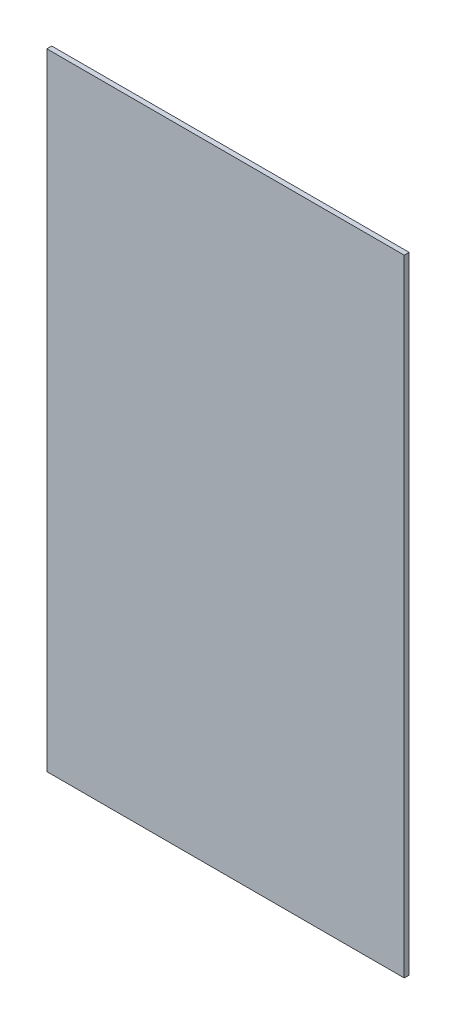
SolidWorks part; units mm, degrees
ref_plane "Plan de face" through (0, 0, 0) normal (0, 0, 1) x (1, 0, 0)
ref_plane "Plan de dessus" through (0, 0, 0) normal (0, 1, 0) x (1, 0, 0)
ref_plane "Plan de droite" through (0, 0, 0) normal (1, 0, 0) x (0, 0, -1)
sketch "Esquisse1" plane through (0, 0, 0) normal (0, 0, 1) x (1, 0, 0)
  line L1 (-237.5, -416) -> (237.5, -416)
  line L2 (-237.5, -416) -> (-237.5, 416)
  line L3 (-237.5, 416) -> (237.5, 416)
  line L4 (237.5, -416) -> (237.5, 416)
  line L5 (-237.5, -416) -> (237.5, 416) construction
  line L6 (-237.5, 416) -> (237.5, -416) construction
  point P0 (0, 0)
  dimension "D1" = 832
  dimension "D2" = 475
extrude "Boss.-Extru.1" add sketch "Esquisse1" along normal blind 6.5
